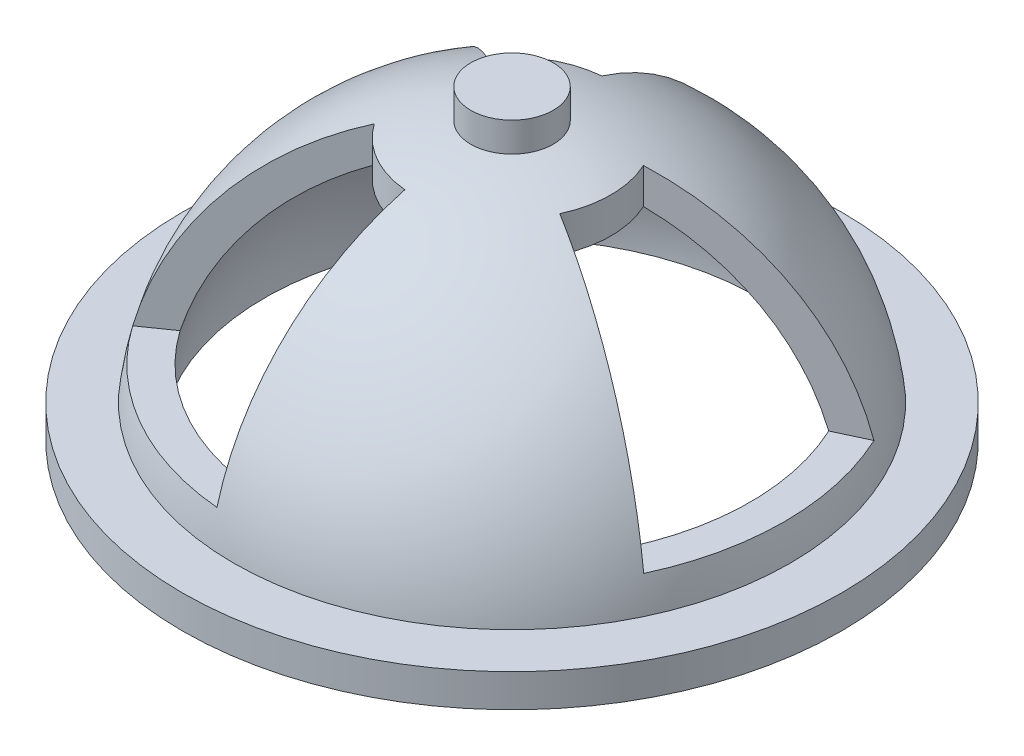
SolidWorks part; units mm, degrees
ref_plane "前视基准面" through (0, 0, 0) normal (0, 0, 1) x (1, 0, 0)
ref_plane "上视基准面" through (0, 0, 0) normal (0, 1, 0) x (1, 0, 0)
ref_plane "右视基准面" through (0, 0, 0) normal (1, 0, 0) x (0, 0, -1)
other "Configuration Table"
sketch "草图1" plane through (0, 0, 0) normal (1, 0, 0) x (0, 0, -1)
  line L0 (0, 46.5) -> (0, 37.5)
  line L1 (-50, 0) -> (-37.5, 0)
  line L2 (-50, 0) -> (-50, 5)
  line L3 (-50, 5) -> (-42.2049, 5)
  line L4 (-6.25, 42.0379) -> (-6.25, 46.5)
  line L11 (-6.25, 46.5) -> (0, 46.5)
  line L12 (0, 58.334) -> (0, -8.5566) construction
  arc A0 (-6.25, 42.0379) -> (-42.2049, 5) centre (0, 0) ccw
  arc A2 (0, 37.5) -> (-37.5, 0) centre (0, 0) ccw
  point P15 (0, 46.5)
  dimension "D1" = 50
  dimension "D2" = 85
  dimension "D3" = 75
  dimension "D4" = 5
  dimension "D5" = 46.5
  dimension "D6" = 6.25
revolve "旋转2" add sketch "草图1" angle 360 about L12
sketch "草图2" plane through (0, 0, 0) normal (0, 1, 0) x (1, 0, 0)
  line L0 (-1.3073, -14.9429) -> (-3.6478, -41.695)
  line L1 (13.5946, 6.3393) -> (37.9328, 17.6884)
  line L2 (13.5946, -6.3393) -> (37.9328, -17.6884)
  line L3 (-12.2873, -8.6036) -> (-34.285, -24.0066)
  line L4 (-12.2873, 8.6036) -> (-34.285, 24.0066)
  line L5 (-1.3073, 14.9429) -> (-3.6478, 41.695)
  arc A0 (13.5946, -6.3393) -> (13.5946, 6.3393) centre (0, 0) ccw
  arc A2 (37.9328, -17.6884) -> (37.9328, 17.6884) centre (0, 0) ccw
  arc A3 (-12.2873, -8.6036) -> (-1.3073, -14.9429) centre (0, 0) ccw
  arc A4 (-34.285, -24.0066) -> (-3.6478, -41.695) centre (0, 0) ccw
  arc A5 (-1.3073, 14.9429) -> (-12.2873, 8.6036) centre (0, 0) ccw
  arc A6 (-3.6478, 41.695) -> (-34.285, 24.0066) centre (0, 0) ccw
  point P17 (0, 0)
  dimension "D1" = 3
  dimension "D2" = 30
  dimension "D4" = 83.7085
  dimension "D3" = 50
extrude "切除-拉伸1" cut sketch "草图2" along normal up to next from offset 10
